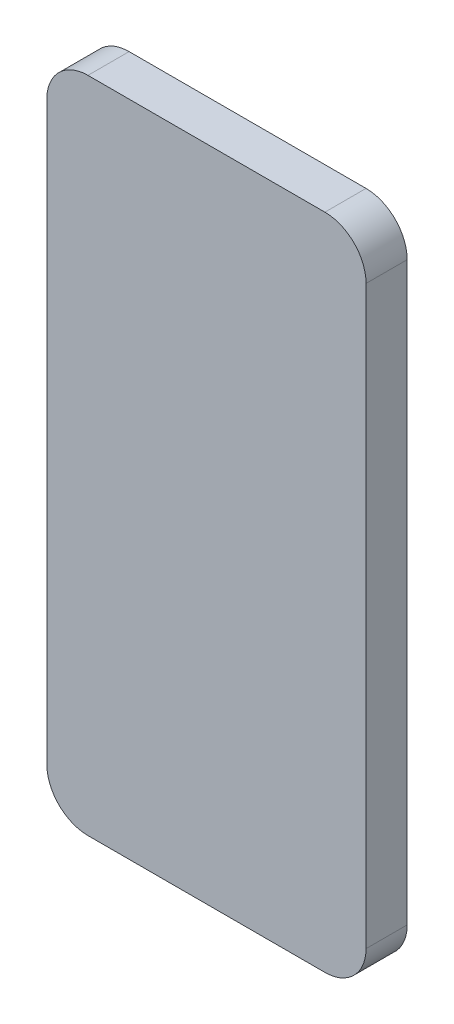
SolidWorks part; units mm, degrees
ref_plane "Front Plane" through (0, 0, 0) normal (0, 0, 1) x (1, 0, 0)
ref_plane "Top Plane" through (0, 0, 0) normal (0, 1, 0) x (1, 0, 0)
ref_plane "Right Plane" through (0, 0, 0) normal (1, 0, 0) x (0, 0, -1)
sketch "Sketch1" plane through (0, 0, 0) normal (0, 0, 1) x (1, 0, 0)
  line L1 (-28.79, 42.9793) -> (28.79, 42.9793)
  line L2 (-38.79, 32.9793) -> (-38.79, -107.0207)
  line L3 (-28.79, -117.0207) -> (28.79, -117.0207)
  line L4 (38.79, 32.9793) -> (38.79, -107.0207)
  arc A0 (28.79, -117.0207) -> (38.79, -107.0207) centre (28.79, -107.0207) ccw
  arc A1 (-38.79, -107.0207) -> (-28.79, -117.0207) centre (-28.79, -107.0207) ccw
  arc A2 (28.79, 42.9793) -> (38.79, 32.9793) centre (28.79, 32.9793) cw
  arc A3 (-28.79, 42.9793) -> (-38.79, 32.9793) centre (-28.79, 32.9793) ccw
  point P0 (0, -37.0207)
  dimension "D3" = 10
extrude "Boss-Extrude1" add sketch "Sketch1" along normal blind 10
